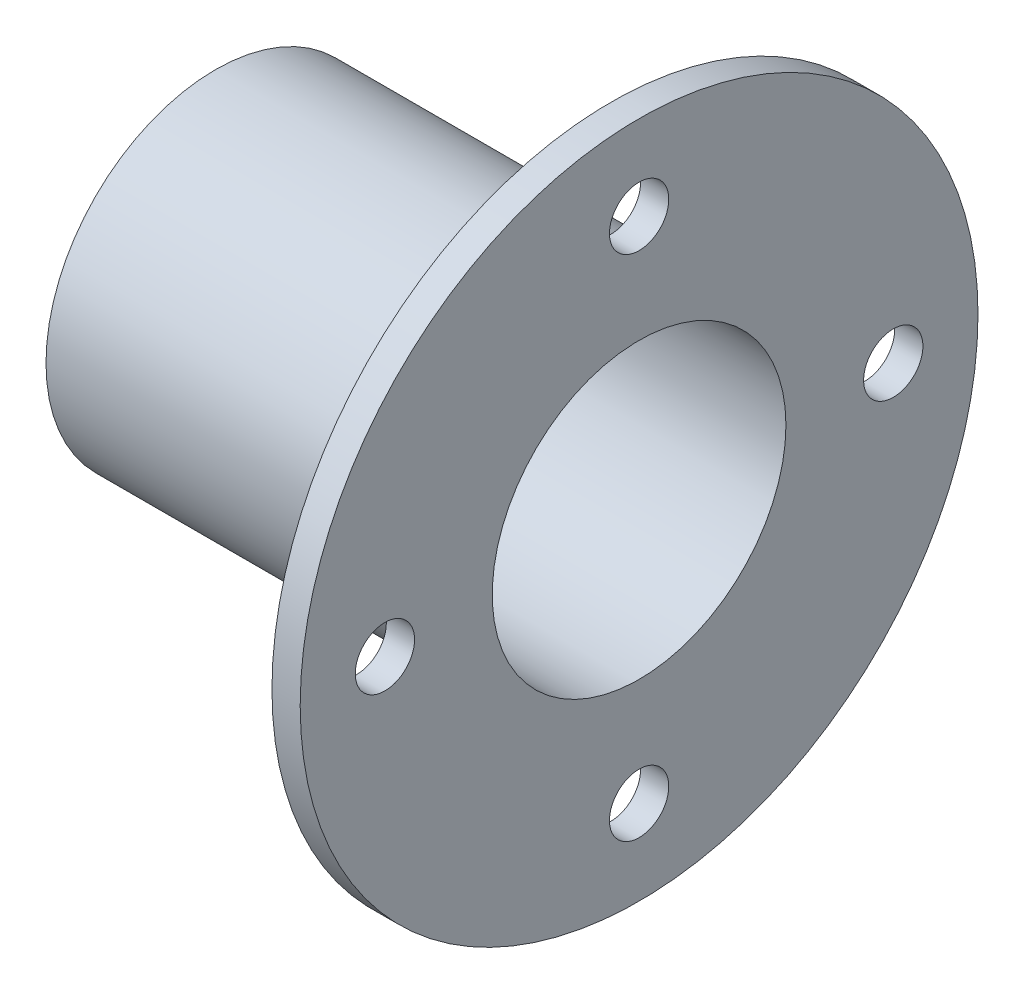
SolidWorks part; units mm, degrees
ref_plane "Płaszczyzna przednia" through (0, 0, 0) normal (0, 0, 1) x (1, 0, 0)
ref_plane "Płaszczyzna górna" through (0, 0, 0) normal (0, 1, 0) x (1, 0, 0)
ref_plane "Płaszczyzna prawa" through (0, 0, 0) normal (1, 0, 0) x (0, 0, -1)
sketch "Szkic1" plane through (0, 0, 0) normal (1, 0, 0) x (0, 0, -1)
  circle A0 centre (0, 0) radius 30
  circle A1 centre (0, 0) radius 26
  dimension "D1" = 52
  dimension "D2" = 60
extrude "Dodanie-wyciągnięcie1" add sketch "Szkic1" along normal blind 70
sketch "Szkic2" plane through (70, 0, 0) normal (1, 0, 0) x (0, 0, -1)
  circle A0 centre (0, 0) radius 60
  circle A2 centre (0, 0) radius 26
  dimension "D1" = 120
  dimension "D2" = 52
extrude "Dodanie-wyciągnięcie2" add sketch "Szkic2" along normal blind 5
sketch "Szkic3" plane through (75, 0, 0) normal (1, 0, 0) x (0, 0, -1)
  line L0 (-45, 0) -> (45, 0) construction
  line L1 (0, -45) -> (0, 45) construction
  circle A0 centre (-45, 0) radius 5.25
  circle A1 centre (45, 0) radius 5.25
  circle A2 centre (0, -45) radius 5.25
  circle A3 centre (0, 45) radius 5.25
  point P8 (0, 0)
  point P9 (0, 0)
  dimension "D3" = 10.5
  dimension "D1" = 90
  dimension "D2" = 90
extrude "Wytnij-wyciągnięcie1" cut sketch "Szkic3" against normal up to surface (5 mm away) up to face at (70, 0, -60)
